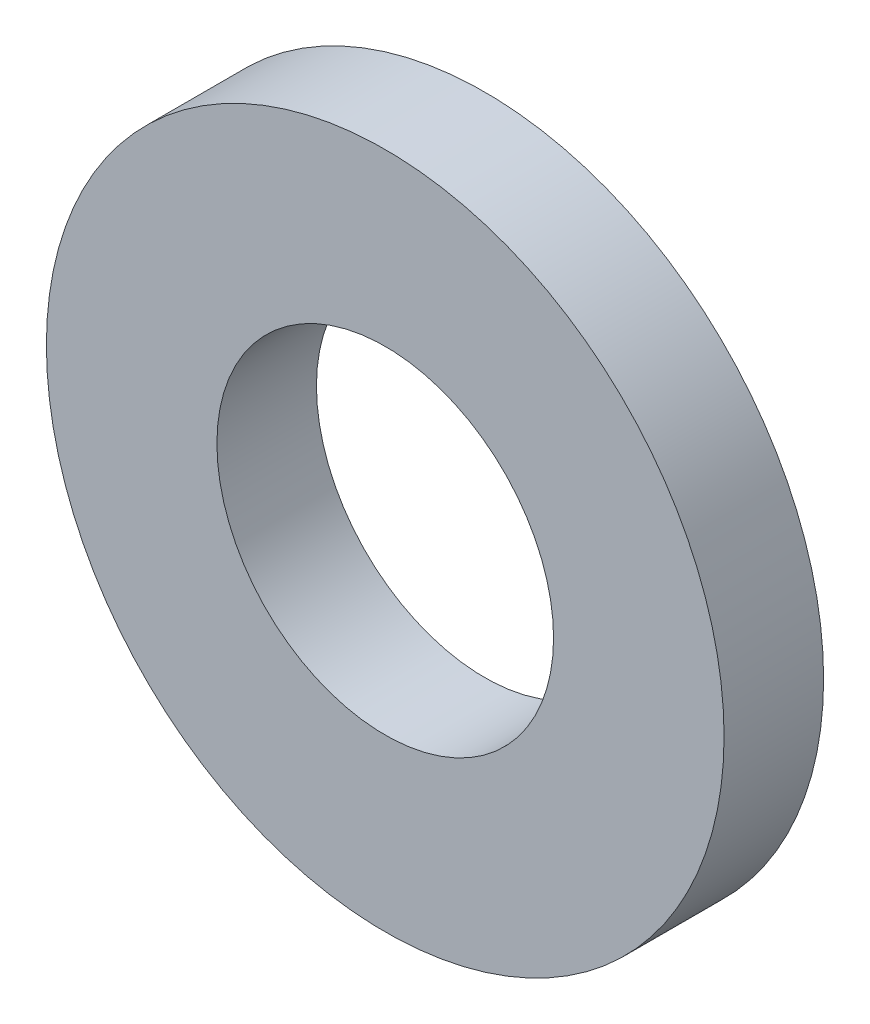
SolidWorks part; units mm, degrees
ref_plane "Piano frontale" through (0, 0, 0) normal (0, 0, 1) x (1, 0, 0)
ref_plane "Piano superiore" through (0, 0, 0) normal (0, 1, 0) x (1, 0, 0)
ref_plane "Piano destro" through (0, 0, 0) normal (1, 0, 0) x (0, 0, -1)
sketch "Schizzo1" plane through (0, 0, 0) normal (0, 0, 1) x (1, 0, 0)
  circle A0 centre (0, 0) radius 2.315
  circle A1 centre (0, 0) radius 1.15
  dimension "D1" = 2.3
  dimension "D2" = 4.63
extrude "Estrusione-Estrusione1" add sketch "Schizzo1" along normal blind 0.68
